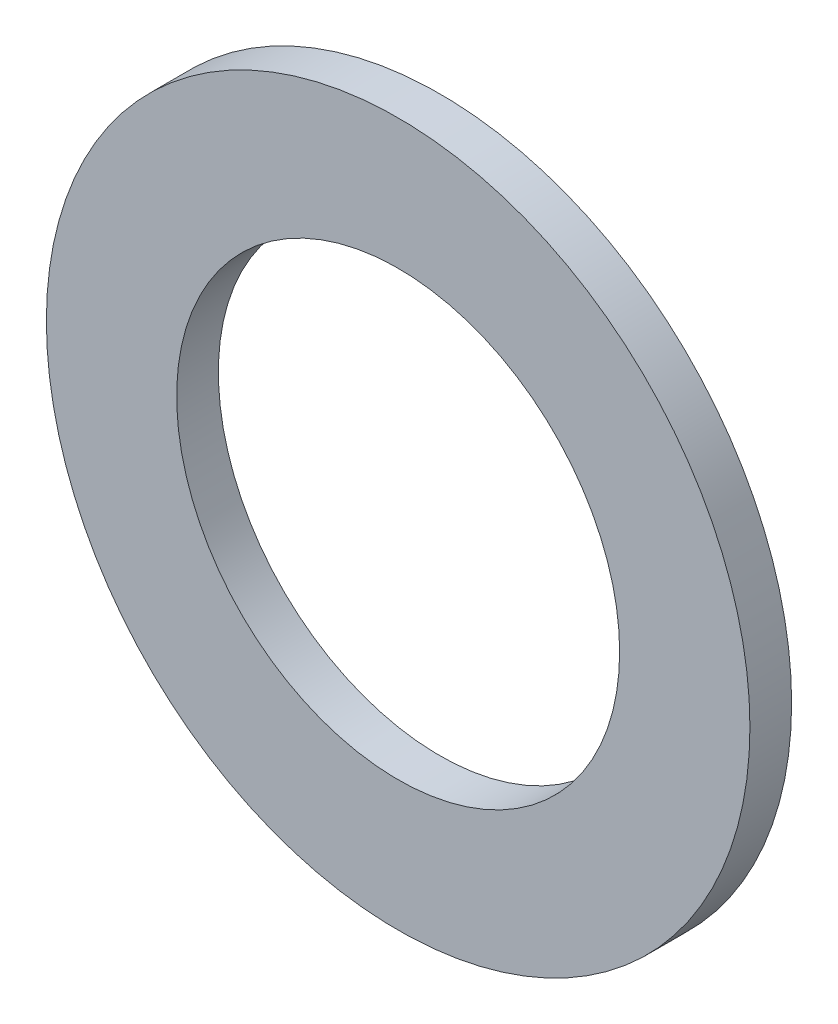
SolidWorks part; units mm, degrees
material "1023 Carbon Steel Sheet (SS)"
ref_plane "Front Plane" through (0, 0, 0) normal (0, 0, 1) x (1, 0, 0)
ref_plane "Top Plane" through (0, 0, 0) normal (0, 1, 0) x (1, 0, 0)
ref_plane "Right Plane" through (0, 0, 0) normal (1, 0, 0) x (0, 0, -1)
sketch "BaseS" plane through (0, 0, 0) normal (0, 0, 1) x (1, 0, 0)
  circle A0 centre (0, 0) radius 4.25
  circle A1 centre (0, 0) radius 6.75
  dimension "OD" = 13.5
  dimension "WasherWidth" = 2.5
extrude "BASE" add sketch "BaseS" along normal mid plane 0.8
